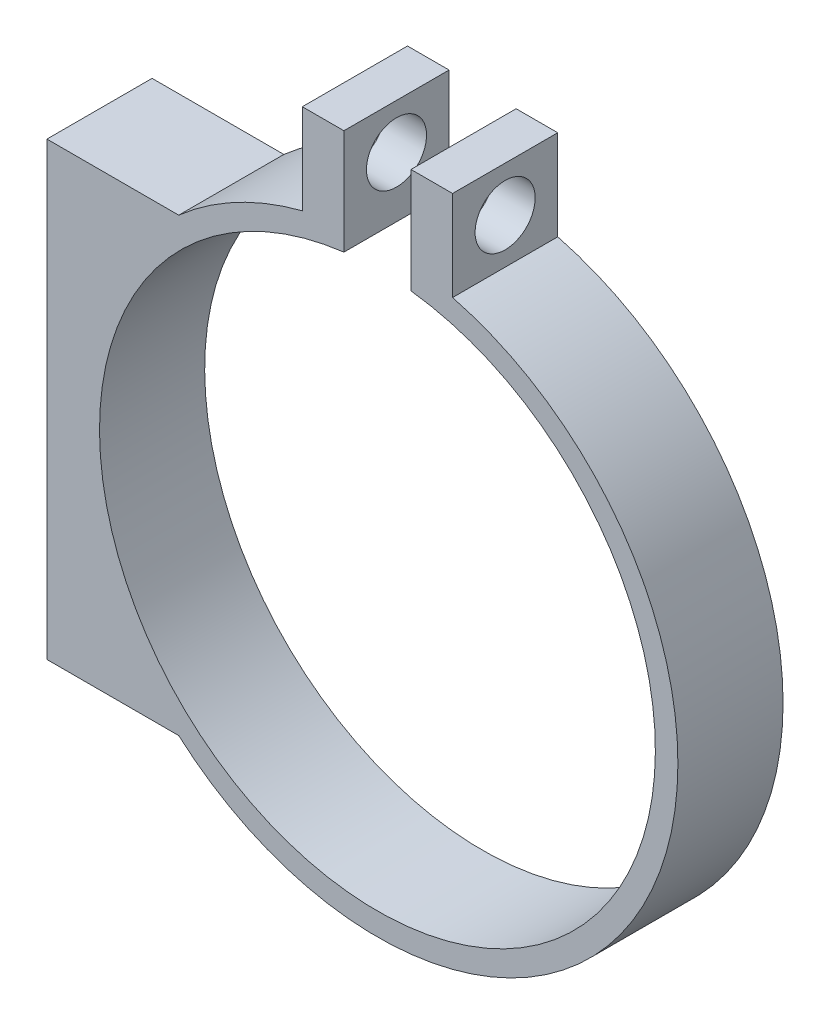
SolidWorks part; units mm, degrees
ref_plane "Front Plane" through (0, 0, 0) normal (0, 0, 1) x (1, 0, 0)
ref_plane "Top Plane" through (0, 0, 0) normal (0, 1, 0) x (1, 0, 0)
ref_plane "Right Plane" through (0, 0, 0) normal (1, 0, 0) x (0, 0, -1)
sketch "Sketch1" plane through (0, 0, 0) normal (0, 0, 1) x (1, 0, 0)
  line L0 (-22, -15) -> (-22, 15)
  line L1 (-22, -15) -> (-13.2288, -15)
  line L2 (-22, 15) -> (-13.2288, 15)
  line L3 (-5, 19.3649) -> (-5, 25.3649)
  line L4 (-5, 25.3649) -> (-2.2316, 25.3649)
  line L5 (5, 25.3649) -> (5, 19.3649)
  line L8 (-2.2316, 25.3649) -> (-2.2316, 18.3649)
  line L9 (2.2316, 25.3649) -> (2.2316, 18.3649)
  line L10 (2.2316, 25.3649) -> (5, 25.3649)
  arc A0 (-13.2288, -15) -> (5, 19.3649) centre (0, 0) ccw
  arc A1 (-2.2316, 18.3649) -> (2.2316, 18.3649) centre (0, 0) ccw
  arc A2 (-5, 19.3649) -> (-13.2288, 15) centre (0, 0) ccw
  dimension "D1" = 40
  dimension "D2" = 37
  dimension "D3" = 22
  dimension "D4" = 30
  dimension "D5" = 15
  dimension "D6" = 10
  dimension "D7" = 5
  dimension "D8" = 6
  dimension "D9" = 7
  dimension "D10" = 7
extrude "Boss-Extrude1" add sketch "Sketch1" along normal blind 7
sketch "Sketch2" plane through (-22, 0, 0) normal (-1, 0, 0) x (0, 0, 1)
  line L0 (7, 15) -> (0, 15) construction
  circle A0 centre (3.5, 12.5) radius 1.75
  circle A1 centre (3.5, -12.5) radius 1.75
  dimension "D3" = 3.5
  dimension "D4" = 3.5
  dimension "D1" = 25
  dimension "D2" = 2.5
extrude "Cut-Extrude2" cut sketch "Sketch2" against normal blind 5
sketch "Sketch3" plane through (-5, 0, 0) normal (-1, 0, 0) x (0, 0, 1)
  circle A0 centre (3.5, 22.3649) radius 2
  dimension "D1" = 4
extrude "Cut-Extrude3" cut sketch "Sketch3" against normal blind 15
